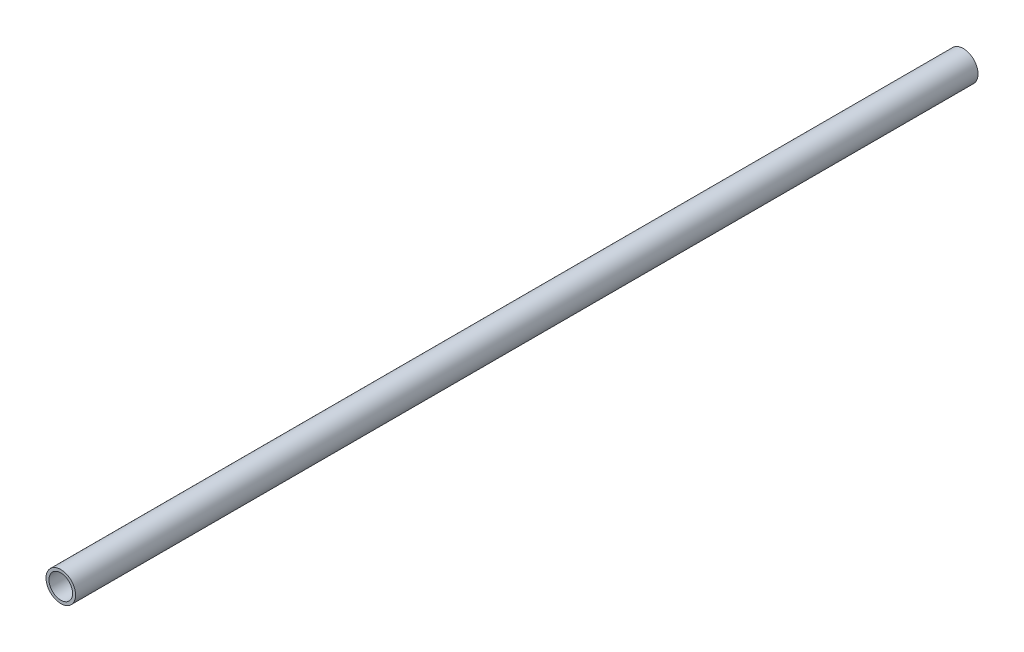
SolidWorks part; units mm, degrees
material "Acciaio al carbonio semplice"
ref_plane "Front" through (0, 0, 0) normal (0, 0, 1) x (1, 0, 0)
ref_plane "Top" through (0, 0, 0) normal (0, 1, 0) x (1, 0, 0)
ref_plane "Right" through (0, 0, 0) normal (1, 0, 0) x (0, 0, -1)
sketch "Schizzo1" plane through (0, 0, 0) normal (0, 0, 1) x (1, 0, 0)
  circle A0 centre (0, 0) radius 15
  circle A1 centre (0, 0) radius 12
  dimension "D1" = 30
  dimension "D2" = 3
extrude "Estrusione-Estrusione1" add sketch "Schizzo1" along normal mid plane 916
